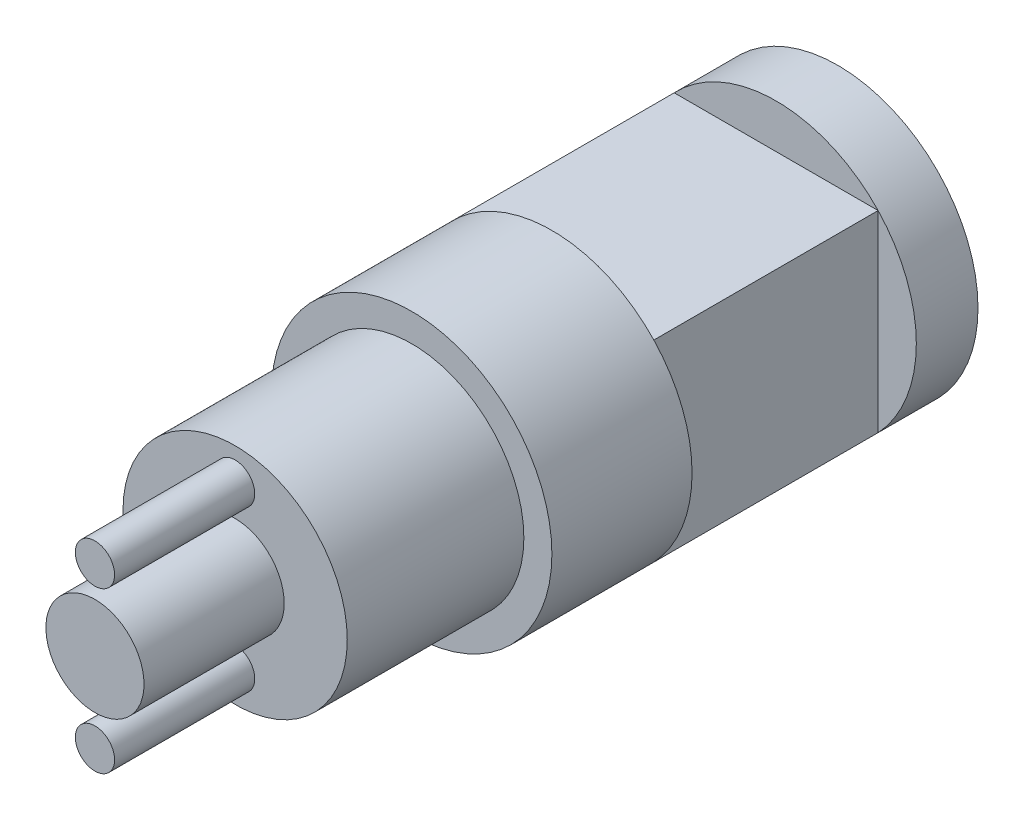
SolidWorks part; units mm, degrees
ref_plane "Front Plane" through (0, 0, 0) normal (0, 0, 1) x (1, 0, 0)
ref_plane "Top Plane" through (0, 0, 0) normal (0, 1, 0) x (1, 0, 0)
ref_plane "Right Plane" through (0, 0, 0) normal (1, 0, 0) x (0, 0, -1)
sketch "Cylinder Face" plane through (0, 0, 0) normal (0, 0, 1) x (1, 0, 0)
  circle A0 centre (0, 0) radius 5
  dimension "D1" = 10
extrude "Base Cylinder" add sketch "Cylinder Face" along normal blind 2.2
sketch "rectangular thing" plane through (0, 0, 2.2) normal (0, 0, 1) x (1, 0, 0)
  line L1 (3.6371, 3.431) -> (-3.6371, 3.431)
  line L2 (3.6371, 3.431) -> (3.6371, -3.431)
  line L3 (3.6371, -3.431) -> (-3.6371, -3.431)
  line L4 (-3.6371, 3.431) -> (-3.6371, -3.431)
  line L5 (3.6371, 3.431) -> (-3.6371, -3.431) construction
  line L6 (3.6371, -3.431) -> (-3.6371, 3.431) construction
  circle A0 centre (0, 0) radius 5 construction
  point P0 (0, 0)
extrude "rectangular" add sketch "rectangular thing" along normal blind 8
sketch "Sketch5" plane through (0, 0, 10.2) normal (0, 0, 1) x (1, 0, 0)
  circle A0 centre (0, 0) radius 5
extrude "2nd Cylinder" add sketch "Sketch5" along normal blind 5
sketch "Sketch6" plane through (0, 0, 15.2) normal (0, 0, 1) x (1, 0, 0)
  circle A0 centre (0, 0) radius 4
  dimension "D1" = 8
extrude "3rd Cylinder" add sketch "Sketch6" along normal blind 6.3 contours A0
sketch "Sketch7" plane through (0, 0, 21.5) normal (0, 0, 1) x (1, 0, 0)
  circle A0 centre (0, 0) radius 1.75
  dimension "D1" = 3.5
extrude "Top Cylinder" add sketch "Sketch7" along normal blind 5
sketch "Sketch9" plane through (0, 0, 21.5) normal (0, 0, 1) x (1, 0, 0)
  line L0 (0, -5.1145) -> (0, 5.2069) construction
  line L1 (-5.8338, 0) -> (6.0054, 0) construction
  circle A0 centre (0, 2.8575) radius 0.7
  circle A1 centre (0, -2.8575) radius 0.7
  dimension "D1" = 1.4
extrude "Prongs?" add sketch "Sketch9" along normal blind 5
sketch "Sketch10" plane through (0, 0, 0) normal (0, 0, -1) x (-1, 0, 0)
  text T0 "LED"
extrude "Cut-Extrude1" cut sketch "Sketch10" against normal blind 1
